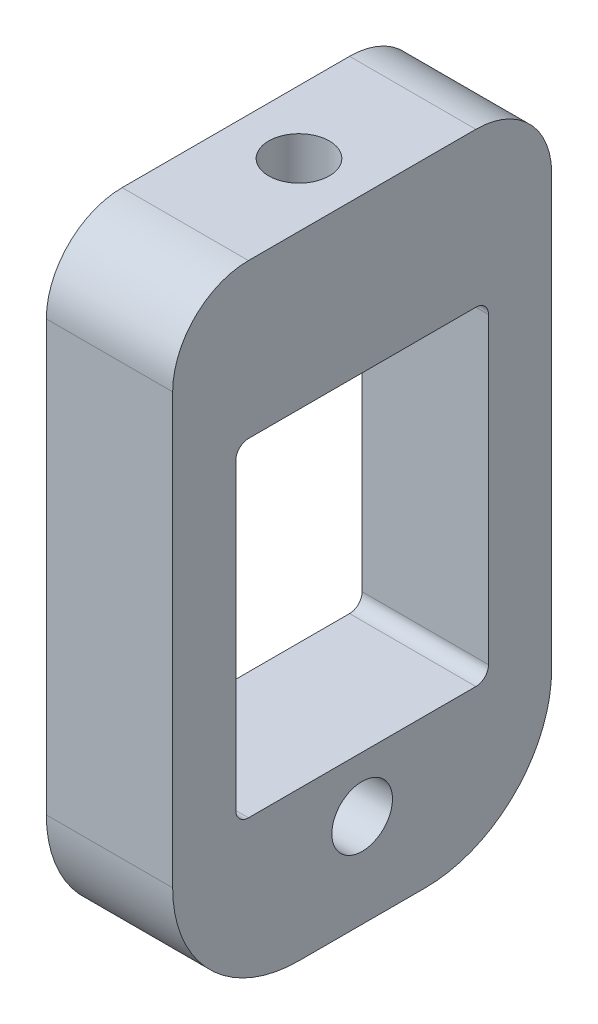
SolidWorks part; units mm, degrees
other "Markup1"
sketch "Sketch6" plane through (-4, 8, -3.5) normal (-0.1216, 0.9914, -0.0475) x (-0.0131, 0.0463, 0.9988)
material "7075 T651 protolabs"
ref_plane "Front Plane" through (0, 0, 0) normal (0, 0, 1) x (1, 0, 0)
ref_plane "Top Plane" through (0, 0, 0) normal (0, 1, 0) x (1, 0, 0)
ref_plane "Right Plane" through (0, 0, 0) normal (1, 0, 0) x (0, 0, -1)
sketch "Sketch16" plane through (0, 0, 0) normal (0, 1, 0) x (1, 0, 0)
  line L1 (-2.5, -7.5) -> (2.5, -7.5)
  line L2 (-2.5, -7.5) -> (-2.5, 7.5)
  line L3 (-2.5, 7.5) -> (2.5, 7.5)
  line L4 (2.5, -7.5) -> (2.5, 7.5)
  line L5 (-2.5, -7.5) -> (2.5, 7.5) construction
  line L6 (-2.5, 7.5) -> (2.5, -7.5) construction
  point P0 (0, 0)
  dimension "D1" = 15
  dimension "D2" = 5
extrude "Main Extrude_Locking" add sketch "Sketch16" along normal blind 25
sketch "Sketch18" plane through (-2.5, 0, 0) normal (-1, 0, 0) x (0, 0, 1)
  line L0 (0, 0) -> (0, 2.5) construction
  line L1 (-7.5, 0) -> (7.5, 0) construction
  circle A0 centre (0, 3.7) radius 1.2
  dimension "D2" = 2.4
  dimension "D1" = 2.5
extrude "Cut-Extrude1" cut sketch "Sketch18" against normal up to surface (5 mm away) up to face at (2.5, 12.5, 0)
sketch "Sketch8" plane through (-2.5, 0, 0) normal (-1, 0, 0) x (0, 0, 1)
  line L0 (0, 4.9) -> (-7.5, 4.9) construction
  line L1 (-7.5, 25) -> (-7.5, 0) construction
  line L3 (5, 5.9) -> (-5, 5.9)
  line L4 (5, 5.9) -> (5, 18.9)
  line L5 (5, 18.9) -> (-5, 18.9)
  line L6 (-5, 5.9) -> (-5, 18.9)
  line L7 (5, 5.9) -> (-5, 18.9) construction
  line L8 (5, 18.9) -> (-5, 5.9) construction
  circle A0 centre (0, 3.7) radius 1.2 construction
  point P6 (0, 12.4)
  dimension "D1" = 2
  dimension "D2" = 13
  dimension "D3" = 10
extrude "Cut-Extrude2" cut sketch "Sketch8" against normal up to surface (5 mm away) up to face at (2.5, 3.7, 1.2)
sketch "Sketch9" plane through (0, 25, 0) normal (0, 1, 0) x (1, 0, 0)
  circle A0 centre (0, 0) radius 1.2
  dimension "D1" = 2.4
extrude "Cut-Extrude3" cut sketch "Sketch9" against normal up to surface (6.1 mm away) up to face at (0, 18.9, 0)
fillet "Fillet1" radius 5 2 edges at (0, 0, 7.5) (0, 0, -7.5)
fillet "Fillet2" radius 3 2 edges at (0, 25, -7.5) (0, 25, 7.5)
fillet "Fillet3" radius 0.5 4 edges at (0, 18.9, 5) (0, 18.9, -5) (0, 5.9, -5) (0, 5.9, 5)
